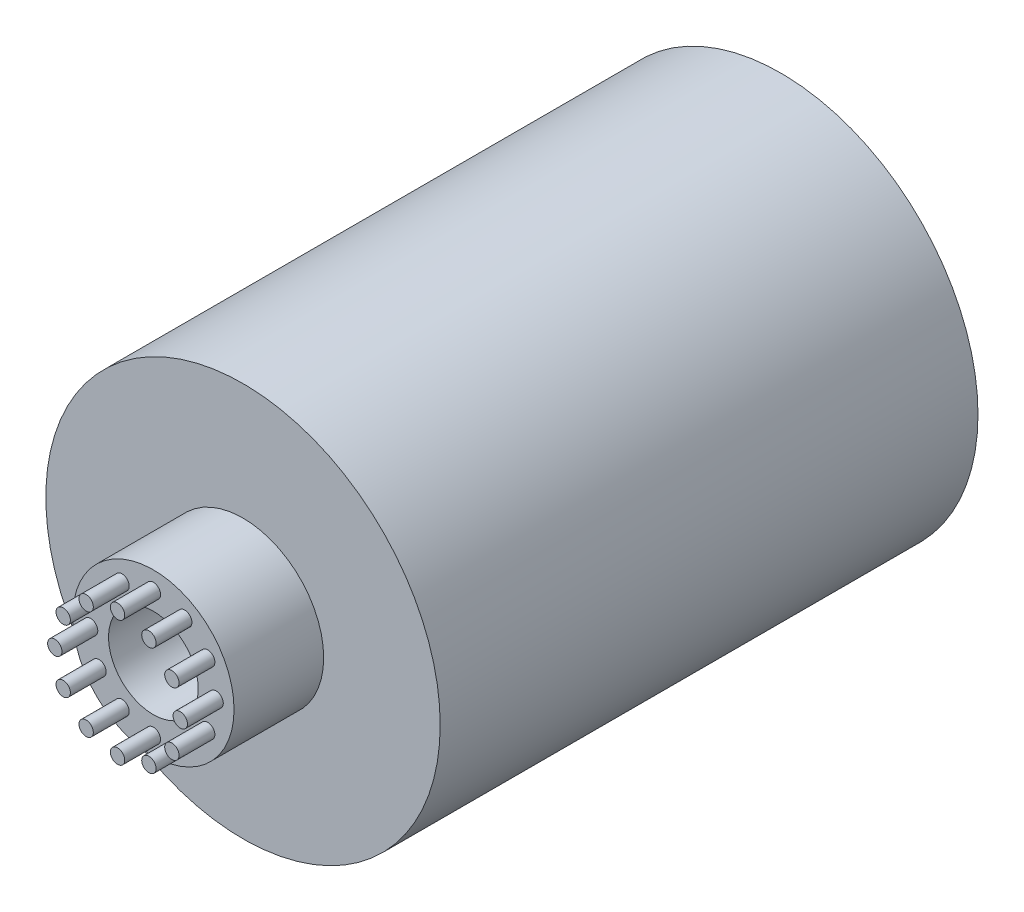
SolidWorks part; units mm, degrees
material "PET"
ref_plane "Front Plane" through (0, 0, 0) normal (0, 0, 1) x (1, 0, 0)
ref_plane "Top Plane" through (0, 0, 0) normal (0, 1, 0) x (1, 0, 0)
ref_plane "Right Plane" through (0, 0, 0) normal (1, 0, 0) x (0, 0, -1)
sketch "Sketch2" plane through (0, 0, 0) normal (0, 0, 1) x (1, 0, 0)
  circle A0 centre (0, 0) radius 11
  dimension "D1" = 22
extrude "Boss-Extrude1" add sketch "Sketch2" along normal blind 30
sketch "Sketch3" plane through (0, 0, 30) normal (0, 0, 1) x (1, 0, 0)
  circle A0 centre (0, 0) radius 4.5
  dimension "D1" = 9
extrude "Boss-Extrude2" add sketch "Sketch3" along normal blind 5
sketch "Sketch4" plane through (0, 0, 0) normal (0, 0, -1) x (-1, 0, 0)
  circle A0 centre (0, 0) radius 4.5
  dimension "D1" = 9
extrude "Boss-Extrude3" add sketch "Sketch4" along normal blind 4
sketch "Sketch5" plane through (0, 0, 35) normal (0, 0, 1) x (1, 0, 0)
  circle A0 centre (0, 0) radius 2.5
  dimension "D1" = 5
extrude "Cut-Extrude1" cut sketch "Sketch5" against normal through all
sketch "Sketch6" plane through (0, 0, 35) normal (0, 0, 1) x (1, 0, 0)
  circle A0 centre (0, 3.5) radius 0.4
  dimension "D1" = 0.8
  dimension "D2" = 3.5
extrude "Boss-Extrude4" add sketch "Sketch6" along normal blind 2
pattern_circular "CirPattern1" count 12 over 360 about axis through (0, 0, 0) along (0, 0, 1) of "Boss-Extrude4"
